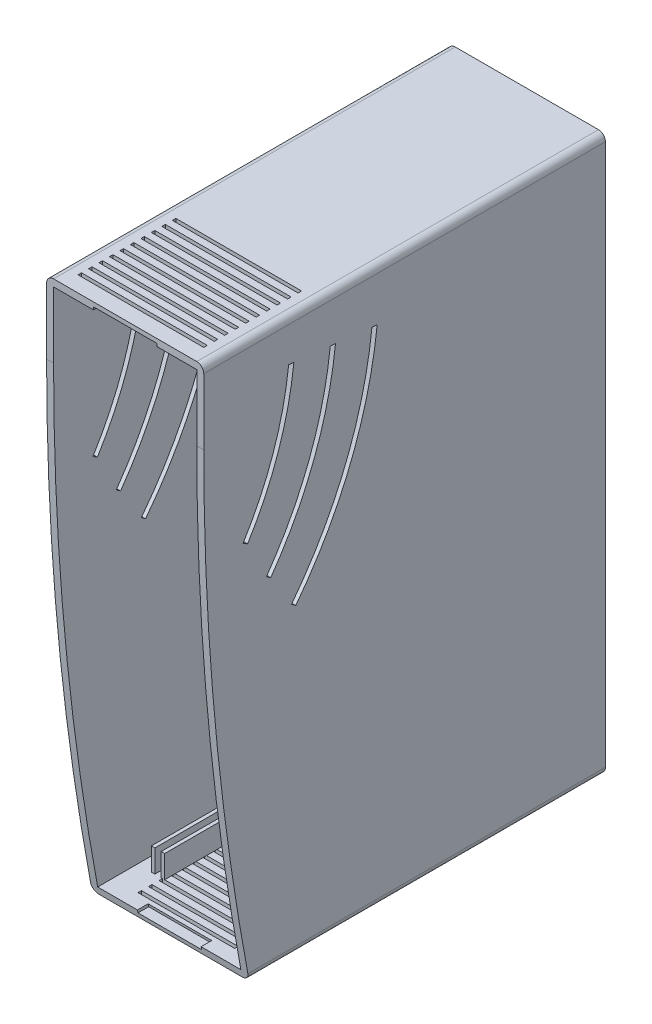
SolidWorks part; units mm, degrees
ref_plane "Front Plane" through (0, 0, 0) normal (0, 0, 1) x (1, 0, 0)
ref_plane "Top Plane" through (0, 0, 0) normal (0, 1, 0) x (1, 0, 0)
ref_plane "Right Plane" through (0, 0, 0) normal (1, 0, 0) x (0, 0, -1)
sketch "Sketch1" plane through (0, 0, 0) normal (0, 0, 1) x (1, 0, 0)
  line L1 (-22.5, -79.55) -> (22.5, -79.55)
  line L2 (-22.5, -79.55) -> (-22.5, 79.55)
  line L3 (-22.5, 79.55) -> (22.5, 79.55)
  line L4 (22.5, -79.55) -> (22.5, 79.55)
  line L5 (-22.5, -79.55) -> (22.5, 79.55) construction
  line L6 (-22.5, 79.55) -> (22.5, -79.55) construction
  point P0 (0, 0)
  dimension "D1" = 45
  dimension "D2" = 159.1
extrude "Boss-Extrude1" add sketch "Sketch1" along normal blind 115
shell "Shell1" thickness 2
sketch "Sketch2" plane through (22.5, 0, 0) normal (1, 0, 0) x (0, 0, -1)
  line L2 (-115, 79.55) -> (-115, 58.65)
  line L3 (-115, -79.55) -> (-115, 79.55) construction
  line L4 (-115, -79.55) -> (0, -79.55) construction
  arc A0 (-115, 58.65) -> (-102, -79.55) centre (626.0862, 58.65) ccw
  dimension "D1" = 20.9
  dimension "D2" = 13
extrude "Cut-Extrude1" cut sketch "Sketch2" along normal through all and the other way through all flip side to cut
fillet "Fillet1" radius 2 4 edges at (-22.5, -79.55, 51) (22.5, -79.55, 51) (-22.5, 79.55, 57.5) (22.5, 79.55, 57.5)
sketch "Sketch3" plane through (0, 79.55, 0) normal (0, 1, 0) x (1, 0, 0)
  line L0 (20.5, -115) -> (-20.5, -115) construction
  line L1 (-18, -109.5) -> (18, -109.5)
  line L2 (-18, -109.5) -> (-18, -110.5)
  line L3 (-18, -110.5) -> (18, -110.5)
  line L4 (18, -109.5) -> (18, -110.5)
  line L5 (-18, -109.5) -> (18, -110.5) construction
  line L6 (-18, -110.5) -> (18, -109.5) construction
  line L7 (0, -115) -> (0, -105.7345) construction
  point P0 (0, -110)
  dimension "D1" = 1
  dimension "D2" = 5
  dimension "D3" = 36
extrude "Cut-Extrude2" cut sketch "Sketch3" against normal blind 4
pattern_linear "LPattern1" count 10 spacing 3 along (0, 0, -1) of "Cut-Extrude2"
sketch "Sketch8" plane through (0, -79.55, 0) normal (0, -1, 0) x (1, 0, 0)
  line L0 (-20.5, 102) -> (20.5, 102) construction
  line L1 (-13.3258, 98) -> (14.3742, 98)
  line L2 (-13.3258, 98) -> (-13.3258, 97)
  line L3 (-13.3258, 97) -> (14.3742, 97)
  line L4 (14.3742, 98) -> (14.3742, 97)
  dimension "D1" = 4
  dimension "D2" = 1
extrude "Cut-Extrude4" cut sketch "Sketch8" against normal blind 5
pattern_linear "LPattern2" count 10 spacing 3 along (0, 0, -1) of "Cut-Extrude4"
sketch "Sketch5" plane through (-22.5, 0, 0) normal (-1, 0, 0) x (0, 0, 1)
  line L0 (65.347, 64.8235) -> (66.8382, 64.9865)
  line L1 (77.276, 66.1274) -> (78.7671, 66.2904)
  line L2 (89.2049, 67.4313) -> (90.6961, 67.5942)
  line L3 (88.6672, 6.884) -> (89.8554, 7.7995)
  line L5 (95.8273, 17.3757) -> (97.0496, 18.2452)
  line L6 (102.4576, 29.0608) -> (103.7315, 29.8528)
  arc A0 (90.6961, 67.5942) -> (103.7315, 29.8528) centre (180.1632, 77.3732) ccw
  arc A1 (89.2049, 67.4313) -> (102.4576, 29.0608) centre (180.1632, 77.3732) ccw
  arc A2 (77.276, 66.1274) -> (95.8273, 17.3757) centre (180.1632, 77.3732) ccw
  arc A3 (78.7671, 66.2904) -> (97.0496, 18.2452) centre (180.1632, 77.3732) ccw
  arc A4 (66.8382, 64.9865) -> (89.8554, 7.7995) centre (180.1632, 77.3732) ccw
  arc A5 (65.347, 64.8235) -> (88.6672, 6.884) centre (180.1632, 77.3732) ccw
  arc A6 (90.6961, 67.5942) -> (108.8676, 22.4466) centre (180.1632, 77.3732) ccw construction
  arc A7 (89.2049, 67.4313) -> (107.6794, 21.5311) centre (180.1632, 77.3732) ccw construction
  arc A8 (78.7671, 66.2904) -> (99.3615, 15.123) centre (180.1632, 77.3732) ccw construction
  arc A9 (77.276, 66.1274) -> (98.1733, 14.2076) centre (180.1632, 77.3732) ccw construction
  dimension "D6" = 90
  dimension "D4" = 12
  dimension "D1" = 1.5
  dimension "D2" = 12
  dimension "D3" = 1.5
  dimension "D5" = 1.5
extrude "Cut-Extrude3" cut sketch "Sketch5" against normal through all
ref_plane "Plane1" through (0, 0, 95) normal (0, 0, 1) x (1, 0, 0)
sketch "Sketch7" plane through (0, 0, 95) normal (0, 0, 1) x (1, 0, 0)
  line L0 (-16.5, 77.55) -> (-16.5, 71.05)
  line L1 (-16.5, 71.05) -> (-15.5, 71.05)
  line L2 (-15.5, 71.05) -> (-15.5, 77.55)
  line L3 (-15.5, 77.55) -> (-16.5, 77.55)
  line L4 (-13.7, 77.55) -> (-13.7, 71.05)
  line L5 (20.5, 77.55) -> (-20.5, 77.55) construction
  line L6 (-13.7, 71.05) -> (-12.7, 71.05)
  line L7 (-12.7, 71.05) -> (-12.7, 77.55)
  line L8 (-12.7, 77.55) -> (-13.7, 77.55)
  line L9 (-20.5, 77.55) -> (-20.5, -77.55) construction
  dimension "D1" = 5
  dimension "D2" = 1
  dimension "D3" = 1.8
  dimension "D4" = 6.5
  dimension "D5" = 1
extrude "Boss-Extrude3" add sketch "Sketch7" against normal blind 90
chamfer "Chamfer2" distance 0.5 angle 45 2 edges at (-13.7, 74.3, 95) (-15.5, 74.3, 95)
sketch "Sketch10" plane through (0, 0, 0) normal (1, 0, 0) x (0, 0, -1)
  line L1 (-131.7092, 78.35) -> (-112, 78.35)
  line L2 (-112, 58.65) -> (-112, 77.55)
  line L3 (-112, 58.65) -> (-112, 78.35)
  line L4 (0, 77.55) -> (-115, 77.55) construction
  line L5 (-102.9238, -78.35) -> (-99.1739, -78.35)
  line L6 (-102.3768, -77.55) -> (0, -77.55) construction
  line L7 (-131.7092, 78.35) -> (-102.9238, -78.35)
  arc A3 (-112, 58.65) -> (-99.4279, -76.9986) centre (626.0862, 58.65) ccw
  arc A4 (-112, 58.65) -> (-99.1739, -78.35) centre (626.0862, 58.65) ccw
  dimension "D2" = 0.8
  dimension "D3" = 0.8
  dimension "D1" = 3
extrude "Cut-Extrude6" cut sketch "Sketch10" against normal mid plane 18.21
sketch "Sketch11" plane through (0, 0, 2) normal (0, 0, 1) x (1, 0, 0)
  line L0 (9.105, -77.55) -> (-9.105, -77.55) construction
  line L1 (-16.5, -77.55) -> (-15.5, -77.55)
  line L2 (-16.5, -77.55) -> (-16.5, -71.05)
  line L3 (-16.5, -71.05) -> (-15.5, -71.05)
  line L4 (-15.5, -77.55) -> (-15.5, -71.05)
  line L5 (-20.5, -77.55) -> (20.5, -77.55) construction
  line L6 (-13.7, -77.55) -> (-12.7, -77.55)
  line L7 (-13.7, -77.55) -> (-13.7, -71.05)
  line L8 (-13.7, -71.05) -> (-12.7, -71.05)
  line L9 (-12.7, -77.55) -> (-12.7, -71.05)
  line L10 (-20.5, 77.55) -> (-20.5, -77.55) construction
  dimension "D1" = 6.5
  dimension "D2" = 6.5
  dimension "D3" = 5
  dimension "D4" = 1
  dimension "D5" = 1.8
  dimension "D6" = 1
extrude "Boss-Extrude6" add sketch "Sketch11" along normal blind 89
sketch "Sketch12" plane through (0, 0, 0) normal (0, 0, -1) x (-1, 0, 0)
  line L0 (1.027, -36.395) -> (16.0066, -36.395)
  line L1 (1.227, -36.195) -> (15.8066, -36.195) construction
  line L2 (1.227, -36.195) -> (1.227, 36.195) construction
  line L3 (1.227, 36.195) -> (15.8066, 36.195) construction
  line L4 (15.8066, -36.195) -> (15.8066, 36.195) construction
  line L5 (16.0066, -36.395) -> (16.0066, 36.395)
  line L6 (1.027, 36.395) -> (16.0066, 36.395)
  line L7 (1.027, -36.395) -> (1.027, 36.395)
  line L8 (3.65, -71.3313) -> (17.7, -71.3313)
  line L9 (3.85, -71.1313) -> (17.5, -71.1313) construction
  line L10 (3.85, -71.1313) -> (3.85, -60.4813) construction
  line L11 (3.85, -60.4813) -> (17.5, -60.4813) construction
  line L12 (17.5, -71.1313) -> (17.5, -60.4813) construction
  line L13 (17.7, -71.3313) -> (17.7, -60.2813)
  line L14 (3.65, -60.2813) -> (17.7, -60.2813)
  line L15 (3.65, -71.3313) -> (3.65, -60.2813)
  line L16 (3.65, 60.27) -> (17.7, 60.27)
  line L17 (3.85, 60.47) -> (17.5, 60.47) construction
  line L18 (3.85, 60.47) -> (3.85, 71.12) construction
  line L19 (3.85, 71.12) -> (17.5, 71.12) construction
  line L20 (17.5, 60.47) -> (17.5, 71.12) construction
  line L21 (17.7, 60.27) -> (17.7, 71.32)
  line L22 (3.65, 71.32) -> (17.7, 71.32)
  line L23 (3.65, 60.27) -> (3.65, 71.32)
  dimension "D1" = 0.2
  dimension "D2" = 0.2
  dimension "D3" = 0.2
extrude "Cut-Extrude7" cut sketch "Sketch12" against normal up to surface (2 mm away) up to face at (-9.7333, -49.5333, 2)
